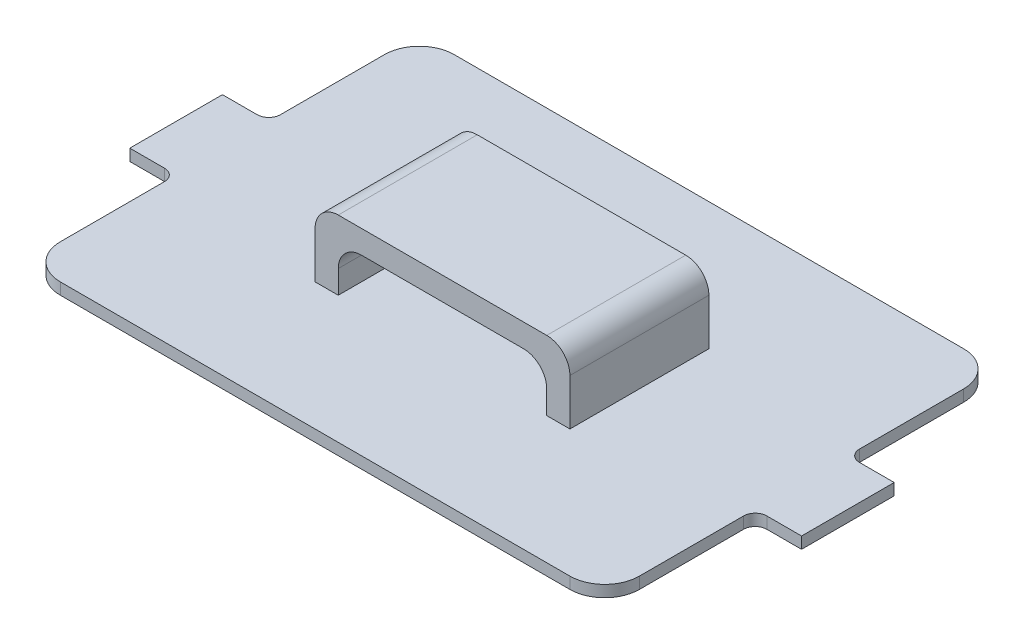
SolidWorks part; units mm, degrees
ref_plane "Front Plane" through (0, 0, 0) normal (0, 0, 1) x (1, 0, 0)
ref_plane "Top Plane" through (0, 0, 0) normal (0, 1, 0) x (1, 0, 0)
ref_plane "Right Plane" through (0, 0, 0) normal (1, 0, 0) x (0, 0, -1)
sketch "Sketch1" plane through (0, 0, 0) normal (0, 1, 0) x (1, 0, 0)
  line L1 (0, 0) -> (125, 0)
  line L2 (0, 0) -> (0, 85)
  line L3 (0, 85) -> (125, 85)
  line L4 (125, 0) -> (125, 85)
  dimension "D1" = 85
  dimension "D2" = 125
extrude "Boss-Extrude1" add sketch "Sketch1" along normal blind 2.5
sketch "Sketch2" plane through (0, 2.5, 0) normal (0, 1, 0) x (1, 0, 0)
  line L0 (0, 85) -> (0, 0) construction
  line L1 (0, 42.5) -> (125, 42.5) construction
  line L2 (0, 42.5) -> (-10, 42.5)
  line L3 (0, 32.5) -> (0, 52.5)
  line L4 (0, 52.5) -> (-10, 52.5)
  line L5 (-10, 32.5) -> (-10, 52.5)
  line L6 (0, 32.5) -> (-10, 32.5)
  line L7 (62.5, 42.5) -> (62.5, 85) construction
  line L8 (125, 32.5) -> (125, 52.5)
  line L9 (125, 52.5) -> (135, 52.5)
  line L10 (135, 32.5) -> (135, 52.5)
  line L11 (125, 32.5) -> (135, 32.5)
  line M8 (0, 85) -> (0, 0)
  line M10 (125, 0) -> (125, 85)
  dimension "D1" = 10
  dimension "D2" = 10
extrude "Boss-Extrude2" add sketch "Sketch2" against normal blind 2.5 contours L11 L10 L9 M10 | L6 L2 L5 M8 | L5 L2 L4 M8
fillet "Fillet1" radius 2.5 4 edges at (125, 1.25, -52.5) (125, 1.25, -32.5) (0, 1.25, -52.5) (0, 1.25, -32.5)
fillet "Fillet2" radius 7.5 4 edges at (125, 1.25, -85) (125, 1.25, 0) (0, 1.25, 0) (0, 1.25, -85)
sketch "Sketch3" plane through (0, 2.5, 0) normal (0, 1, 0) x (1, 0, 0)
  line L0 (7.5, 85) -> (7.5, 0) construction
  line L1 (7.5, 0) -> (117.5, 85) construction
  line L2 (117.5, 85) -> (117.5, 0) construction
  line L3 (117.5, 0) -> (7.5, 85) construction
  line L4 (62.5, 42.5) -> (7.5, 42.5) construction
  line L5 (62.5, 42.5) -> (117.5, 42.5) construction
  line L6 (7.5, 42.5) -> (35, 42.5)
  line L7 (35, 42.5) -> (90.6497, 42.5)
  line L8 (90.6497, 42.5) -> (117.5, 42.5)
  line L9 (35, 27.5) -> (40, 27.5)
  line L10 (35, 42.5) -> (40, 42.5)
  line L11 (35, 27.5) -> (35, 57.5)
  line L12 (35, 57.5) -> (40, 57.5)
  line L13 (40, 27.5) -> (40, 57.5)
  line L14 (62.5, 42.5) -> (62.5, 85) construction
  line L15 (90, 27.5) -> (90, 57.5)
  line L16 (90, 57.5) -> (85, 57.5)
  line L17 (85, 27.5) -> (85, 57.5)
  line L18 (90, 27.5) -> (85, 27.5)
  dimension "D1" = 15
  dimension "D2" = 5
  dimension "D3" = 22.5
extrude "Boss-Extrude3" add sketch "Sketch3" along normal blind 15 contours L7 L13 L12 L11 | L9 L13 L7 L11 | L17 L7 L15 L16 | L18 L15 L7 L17
sketch "Sketch4" plane through (40, 0, 0) normal (1, 0, 0) x (0, 0, -1)
  line L1 (27.5, 17.5) -> (57.5, 17.5)
  line L2 (27.5, 17.5) -> (27.5, 12.5)
  line L3 (27.5, 12.5) -> (57.5, 12.5)
  line L4 (57.5, 17.5) -> (57.5, 12.5)
  point P4 (0, 0)
  dimension "D2" = 5
extrude "Boss-Extrude4" add sketch "Sketch4" along normal up to next
fillet "Fillet3" radius 5 4 edges at (85, 12.5, -42.5) (40, 12.5, -42.5) (90, 17.5, -42.5) (35, 17.5, -42.5)
